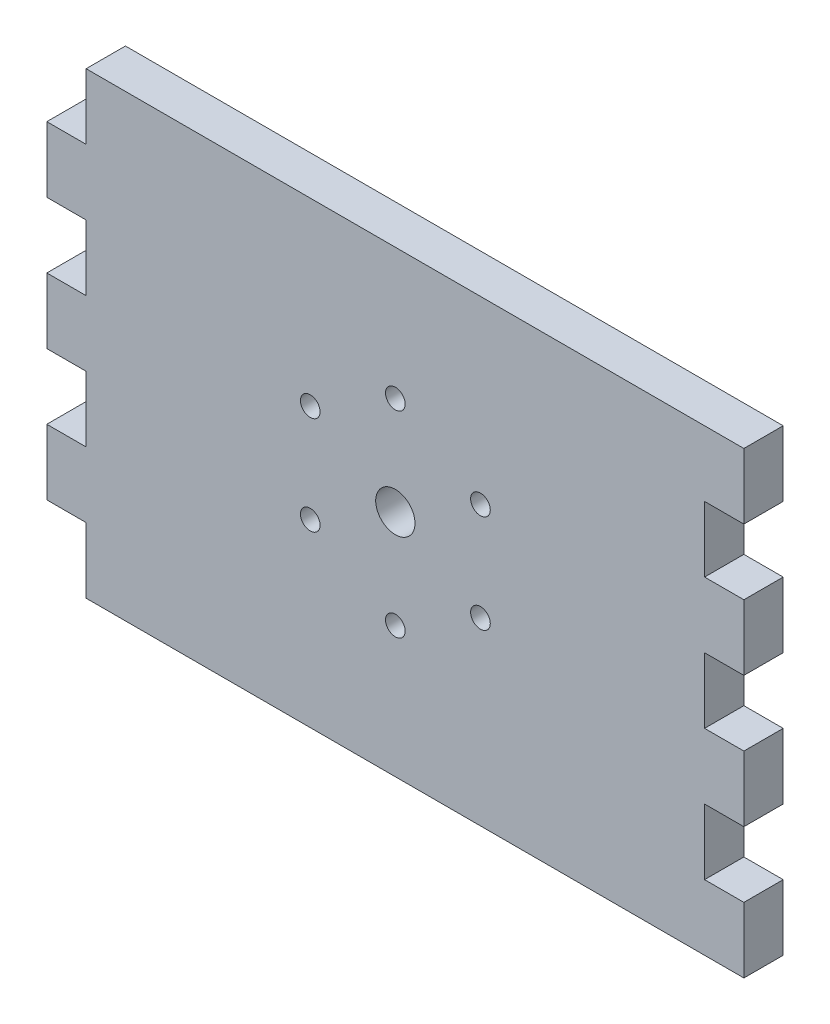
SolidWorks part; units mm, degrees
ref_plane "Alzado" through (0, 0, 0) normal (0, 0, 1) x (1, 0, 0)
ref_plane "Planta" through (0, 0, 0) normal (0, 1, 0) x (1, 0, 0)
ref_plane "Vista lateral" through (0, 0, 0) normal (1, 0, 0) x (0, 0, -1)
sketch "Croquis1" plane through (0, 0, 0) normal (0, 0, 1) x (1, 0, 0)
  line L0 (26.6, 2.5) -> (26.6, 7.5)
  line L1 (-23.6, -17.5) -> (26.6, -17.5)
  line L2 (-26.6, -12.5) -> (-26.6, -7.5)
  line L3 (-23.6, 17.5) -> (26.5813, 17.5)
  line L4 (26.6, -17.5) -> (26.6, -12.5)
  line L5 (-26.6, -17.5) -> (26.6, 17.5) construction
  line L6 (-26.6, 17.5) -> (26.6, -17.5) construction
  line L7 (23.6, -12.5) -> (26.6, -12.5)
  line L8 (23.6, -12.5) -> (23.6, -7.5)
  line L9 (23.6, -7.5) -> (26.6, -7.5)
  line L10 (-23.6, 7.5) -> (-26.6, 7.5)
  line L11 (23.6, -12.5) -> (26.6, -7.5) construction
  line L12 (23.6, -7.5) -> (26.6, -12.5) construction
  line L13 (23.6, -2.5) -> (26.6, -2.5)
  line L14 (23.6, -2.5) -> (23.6, 2.5)
  line L15 (23.6, 2.5) -> (26.6, 2.5)
  line L16 (26.6, -7.5) -> (26.6, -2.5)
  line L17 (23.6, -2.5) -> (26.6, 2.5) construction
  line L18 (23.6, 2.5) -> (26.6, -2.5) construction
  line L19 (23.6, 12.5) -> (26.6, 12.5)
  line L20 (-26.6, 17.5) -> (-23.6, 17.5) construction
  line L21 (-23.6, -17.5) -> (-23.6, -12.5)
  line L23 (23.6, 12.5) -> (26.6, 17.5) construction
  line L25 (0, -17.5) -> (0, 17.5) construction
  line L26 (-26.6, 7.5) -> (-26.6, 12.5)
  line L27 (-23.6, 12.5) -> (-23.6, 17.5)
  line L28 (-23.6, 2.5) -> (-23.6, 7.5)
  line L29 (-23.6, 12.5) -> (-26.6, 12.5)
  line L30 (-26.6, -2.5) -> (-26.6, 2.5)
  line L31 (-23.6, 2.5) -> (-26.6, 2.5)
  line L32 (26.6, 7.5) -> (23.6, 7.5)
  line L33 (-23.6, -2.5) -> (-26.6, -2.5)
  line L34 (23.6, 7.5) -> (23.6, 12.5)
  line L35 (-23.6, -7.5) -> (-26.6, -7.5)
  line L37 (-23.6, -12.5) -> (-26.6, -12.5)
  line L38 (-26.6, -17.5) -> (-26.6, 17.5) construction
  line L39 (26.6, 17.5) -> (26.6, -17.5) construction
  line L40 (26.6, 12.5) -> (26.6, 17.5)
  line L41 (-26.6, -17.5) -> (26.6, -17.5) construction
  line L42 (-23.6, -7.5) -> (-23.6, -2.5)
  line L43 (26.6, 17.5) -> (26.5813, 17.5)
  point P0 (0, 0)
  point P6 (25.1, -10)
  point P11 (25.1, 0)
  point P16 (25.5105, 17.5)
  point P38 (0, 0)
  point P39 (0, 0)
  point P40 (0, 0)
  dimension "D1" = 53.2
  dimension "D2" = 35
  dimension "D3" = 3
  dimension "D4" = 5
  dimension "D5" = 5
  dimension "D6" = 5
  dimension "D7" = 5
  dimension "D8" = 5
  dimension "D9" = 5
extrude "Saliente-Extruir1" add sketch "Croquis1" along normal blind 3
sketch "Croquis2" plane through (0, 0, 3) normal (0, 0, 1) x (1, 0, 0)
  line L0 (0, 17.5) -> (0, -17.5) construction
  line L1 (26.6, 17.5) -> (-23.6, 17.5) construction
  line L2 (-23.6, -17.5) -> (26.6, -17.5) construction
  line L3 (0, 0) -> (0, 7.5) construction
  circle A0 centre (0, 7.5) radius 0.75
  circle A1 centre (6.4952, 3.75) radius 0.75
  circle A2 centre (6.4952, -3.75) radius 0.75
  circle A3 centre (0, -7.5) radius 0.75
  circle A4 centre (-6.4952, -3.75) radius 0.75
  circle A5 centre (-6.4952, 3.75) radius 0.75
  circle A6 centre (0, 0) radius 1.5
  dimension "D1" = 1.5
  dimension "D5" = 3
  dimension "D2" = 7.5
  dimension "D4" = 7.5
  dimension "D3" = 6
extrude "Cortar-Extruir1" cut sketch "Croquis2" against normal up to next
